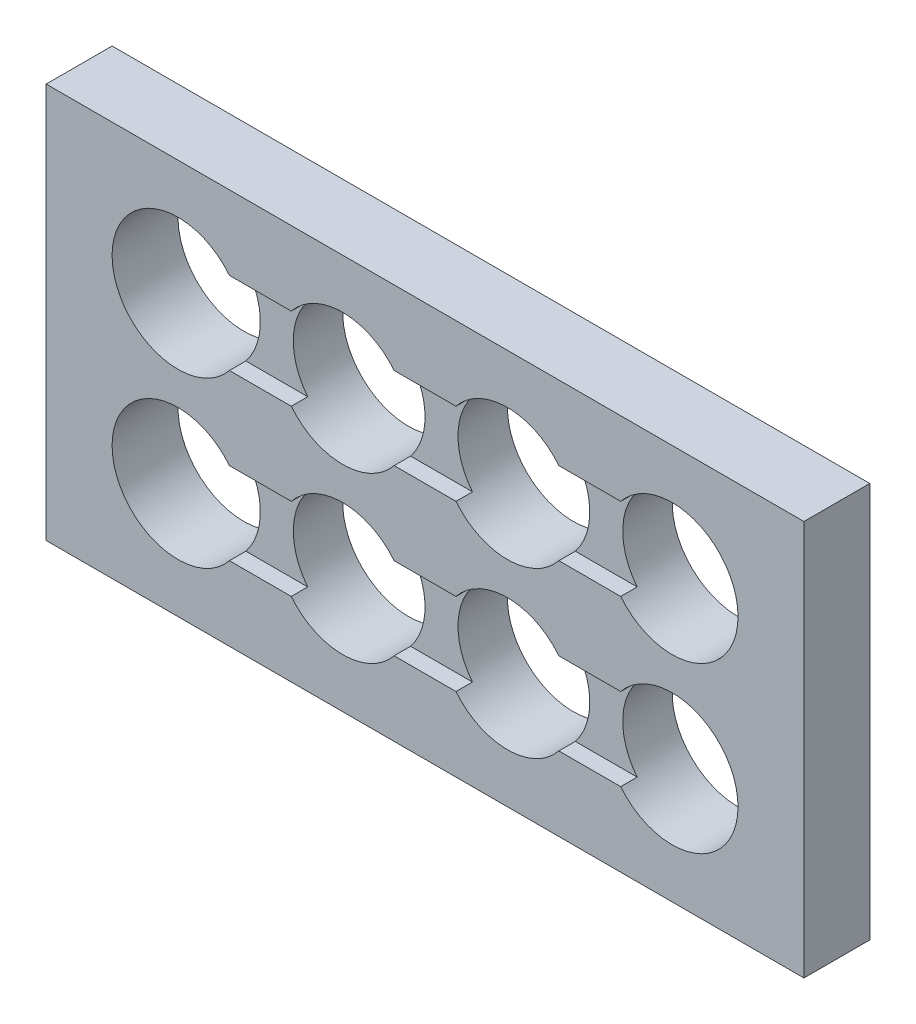
SolidWorks part; units mm, degrees
ref_plane "Přední rovina" through (0, 0, 0) normal (0, 0, 1) x (1, 0, 0)
ref_plane "Horní rovina" through (0, 0, 0) normal (0, 1, 0) x (1, 0, 0)
ref_plane "Pravá rovina" through (0, 0, 0) normal (1, 0, 0) x (0, 0, -1)
sketch "Skica1" plane through (0, 0, 0) normal (0, 0, 1) x (1, 0, 0)
  line L0 (0, 0) -> (23, 0) construction
  line L1 (0, 0) -> (0, 12) construction
  line L2 (-23, 12) -> (23, 12)
  line L3 (23, 12) -> (23, -12)
  line L4 (-23, 12) -> (-23, -12)
  line L5 (-23, -12) -> (23, -12)
  line L6 (-15, -5) -> (-15, -12) construction
  line L7 (-15, -5) -> (-23, -5) construction
  line L8 (15, -5) -> (15, 5) construction
  line L9 (-15, 5) -> (15, 5) construction
  circle A0 centre (-15, -5) radius 4
  circle A1 centre (-5, -5) radius 4
  circle A2 centre (5, -5) radius 4
  circle A3 centre (15, -5) radius 4
  circle A4 centre (-5, 5) radius 4
  circle A5 centre (5, 5) radius 4
  circle A6 centre (15, 5) radius 4
  circle A7 centre (-15, 5) radius 4
  point P9 (-23, 0)
  dimension "D3" = 7
  dimension "D5" = 4
  dimension "D7" = 10
  dimension "D8" = 10
  dimension "D9" = 8
  dimension "D1" = 46
  dimension "D2" = 24
  dimension "D4" = 8
  dimension "D6" = 2
extrude "Přidat vysunutím1" add sketch "Skica1" along normal blind 4
sketch "Skica2" plane through (0, 0, 4) normal (0, 0, 1) x (1, 0, 0)
  line L0 (0, 0) -> (0, 7.5) construction
  line L1 (15, 2.5) -> (15, 7.5)
  line L2 (15, 5) -> (0, 5) construction
  line L3 (15, 7.5) -> (-15, 7.5)
  line L4 (0, 0) -> (14.7437, 0) construction
  line L5 (15, 2.5) -> (-15, 2.5)
  line L6 (-15, 2.5) -> (-15, 7.5)
  line L7 (15, -2.5) -> (15, -7.5)
  line L8 (15, -2.5) -> (-15, -2.5)
  line L9 (-15, -2.5) -> (-15, -7.5)
  line L10 (15, -7.5) -> (-15, -7.5)
  point P14 (0, 2.5)
  dimension "D1" = 5
extrude "Odebrat vysunutím1" cut sketch "Skica2" against normal blind 1
